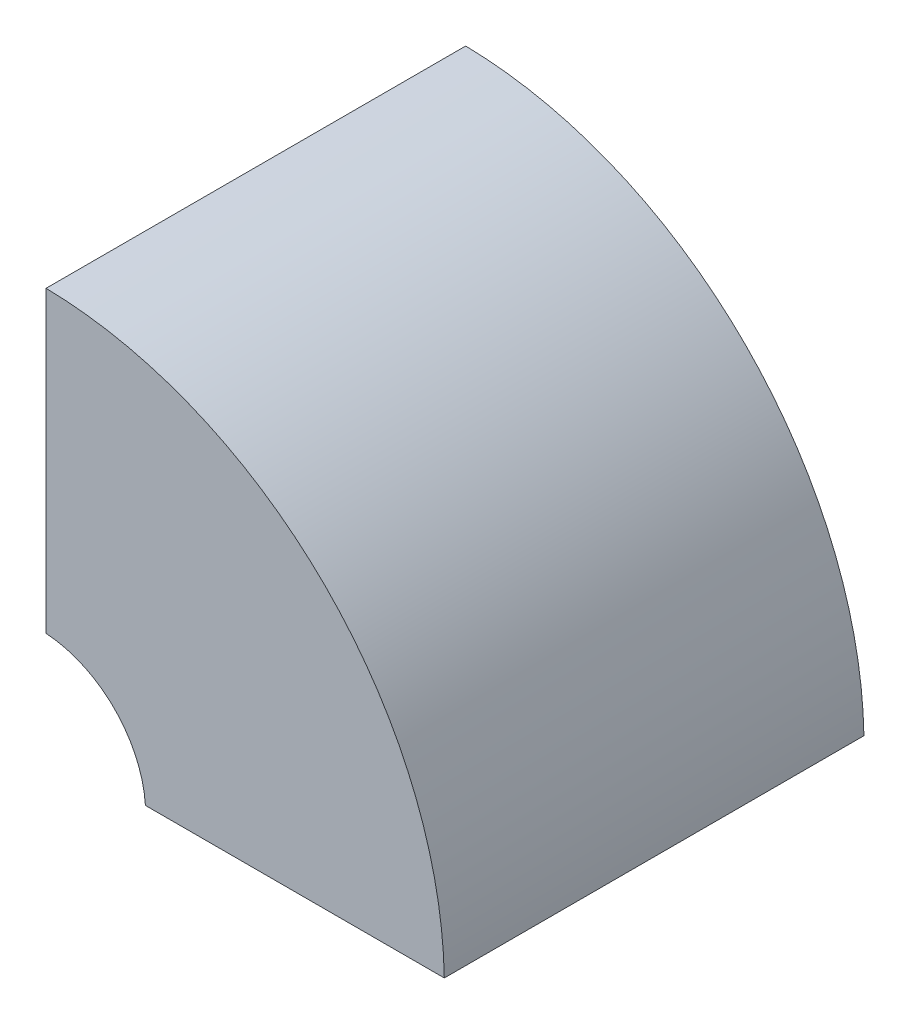
SolidWorks part; units mm, degrees
ref_plane "Front Plane" through (0, 0, 0) normal (0, 0, 1) x (1, 0, 0)
ref_plane "Top Plane" through (0, 0, 0) normal (0, 1, 0) x (1, 0, 0)
ref_plane "Right Plane" through (0, 0, 0) normal (1, 0, 0) x (0, 0, -1)
sketch "Sketch1" plane through (0, 0, 0) normal (0, 0, 1) x (1, 0, 0)
  line L0 (0.5, 28.4956) -> (0.5, 7.4833)
  line L1 (7.4833, 0.5) -> (28.4956, 0.5)
  arc A0 (7.4833, 0.5) -> (0.5, 7.4833) centre (0, 0) ccw
  arc A1 (28.4956, 0.5) -> (0.5, 28.4956) centre (0, 0) ccw
extrude "Boss-Extrude1" add sketch "Sketch1" against normal up to surface (29.5 mm away)
